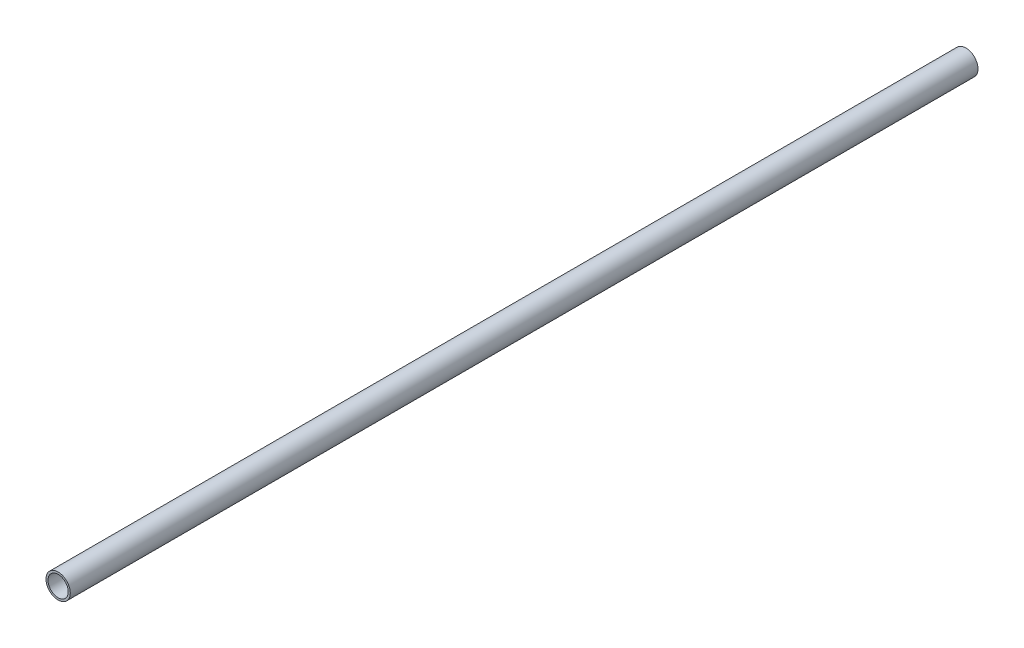
SolidWorks part; units mm, degrees
ref_plane "Ön Düzlem" through (0, 0, 0) normal (0, 0, 1) x (1, 0, 0)
ref_plane "Üst Düzlem" through (0, 0, 0) normal (0, 1, 0) x (1, 0, 0)
ref_plane "Sağ Düzlem" through (0, 0, 0) normal (1, 0, 0) x (0, 0, -1)
sketch "Çizim1" plane through (0, 0, 0) normal (0, 0, 1) x (1, 0, 0)
  circle A0 centre (0, 0) radius 9
  dimension "D1" = 18
extrude "Yükseklik-Ekstrüzyon1" add sketch "Çizim1" along normal blind 672.24
sketch "Çizim2" plane through (0, 0, 0) normal (0, 0, -1) x (-1, 0, 0)
  circle A0 centre (0, 0) radius 7.5
extrude "Kes-Ekstrüzyon1" cut sketch "Çizim2" against normal blind 672.24
